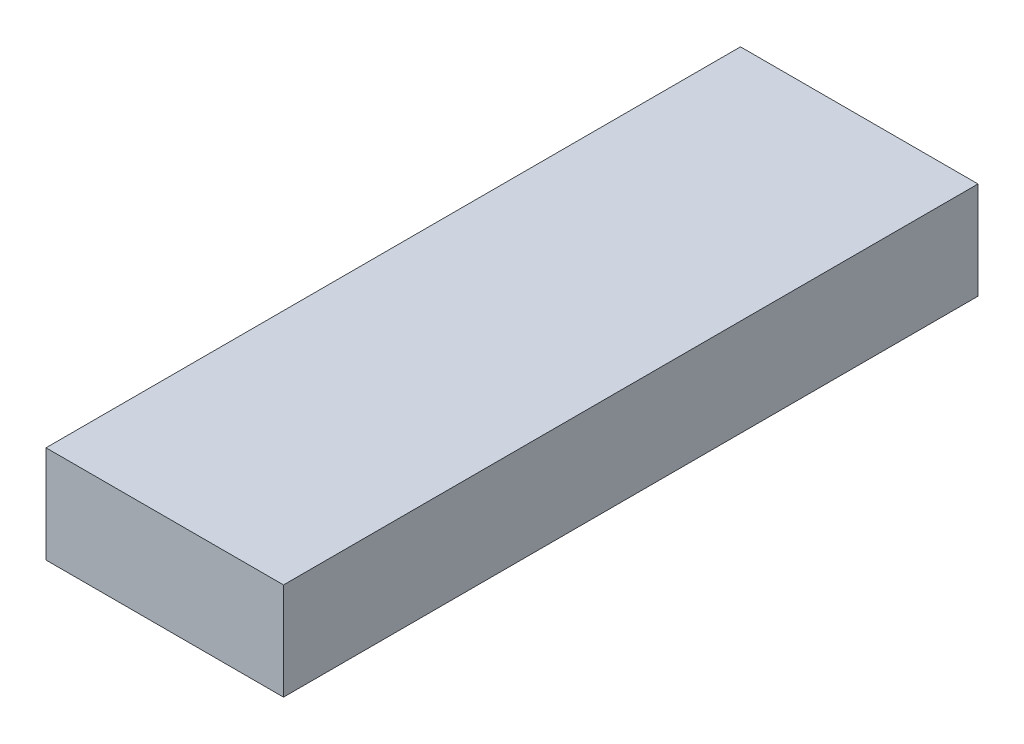
SolidWorks part; units mm, degrees
ref_plane "Front Plane" through (0, 0, 0) normal (0, 0, 1) x (1, 0, 0)
ref_plane "Top Plane" through (0, 0, 0) normal (0, 1, 0) x (1, 0, 0)
ref_plane "Right Plane" through (0, 0, 0) normal (1, 0, 0) x (0, 0, -1)
sketch "Sketch1" plane through (0, 0, 0) normal (0, 0, 1) x (1, 0, 0)
  line L1 (-1.71, 0.7) -> (1.71, 0.7)
  line L2 (-1.71, 0.7) -> (-1.71, -0.7)
  line L3 (-1.71, -0.7) -> (1.71, -0.7)
  line L4 (1.71, 0.7) -> (1.71, -0.7)
  line L5 (-1.71, 0.7) -> (1.71, -0.7) construction
  line L6 (-1.71, -0.7) -> (1.71, 0.7) construction
  point P0 (0, 0)
  dimension "D1" = 3.42
  dimension "D2" = 1.4
extrude "Boss-Extrude1" add sketch "Sketch1" along normal blind 10
